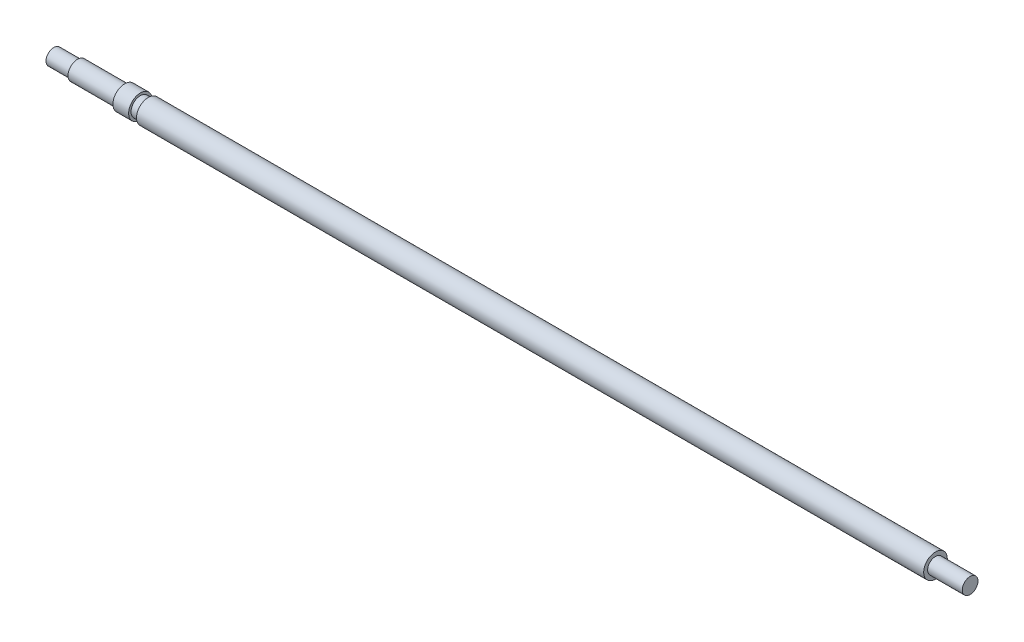
SolidWorks part; units mm, degrees
ref_plane "前视基准面" through (0, 0, 0) normal (0, 0, 1) x (1, 0, 0)
ref_plane "上视基准面" through (0, 0, 0) normal (0, 1, 0) x (1, 0, 0)
ref_plane "右视基准面" through (0, 0, 0) normal (1, 0, 0) x (0, 0, -1)
sketch "草图2" plane through (0, 0, 0) normal (0, 0, 1) x (1, 0, 0)
  line L0 (4565.1199, 584.3322) -> (3983.1199, 584.3322) construction
  line L1 (3983.1199, 589.3322) -> (3998.1199, 589.3322)
  line L2 (3983.1199, 589.3322) -> (3983.1199, 584.3322)
  line L3 (3998.1199, 589.3322) -> (3998.1199, 590.3322)
  line L4 (3998.1199, 590.3322) -> (4028.1199, 590.3322)
  line L5 (4028.1199, 590.3322) -> (4028.1199, 591.8322)
  line L6 (4028.1199, 591.8322) -> (4038.1199, 591.8322)
  line L7 (4038.1199, 590.3322) -> (4038.1199, 591.8322)
  line L8 (4038.1199, 590.3322) -> (4043.1199, 590.3322)
  line L9 (4043.1199, 590.3322) -> (4043.1199, 591.8322)
  line L10 (4043.1199, 591.8322) -> (4543.1199, 591.8322)
  line L11 (4543.1199, 591.8322) -> (4543.1199, 589.3322)
  line L12 (4543.1199, 589.3322) -> (4565.1199, 589.3322)
  line L13 (4565.1199, 589.3322) -> (4565.1199, 584.3322)
  line L14 (4565.1199, 584.3322) -> (3983.1199, 584.3322)
  dimension "D2" = 10
  dimension "D3" = 12
  dimension "D4" = 15
  dimension "D5" = 12
  dimension "D6" = 15
  dimension "D7" = 15
  dimension "D8" = 30
  dimension "D9" = 10
  dimension "D10" = 15
  dimension "D11" = 500
  dimension "D12" = 22
  dimension "D13" = 10
revolve "旋转1" add sketch "草图2" angle 360 about L0
cosmetic thread "装饰螺纹线1"
